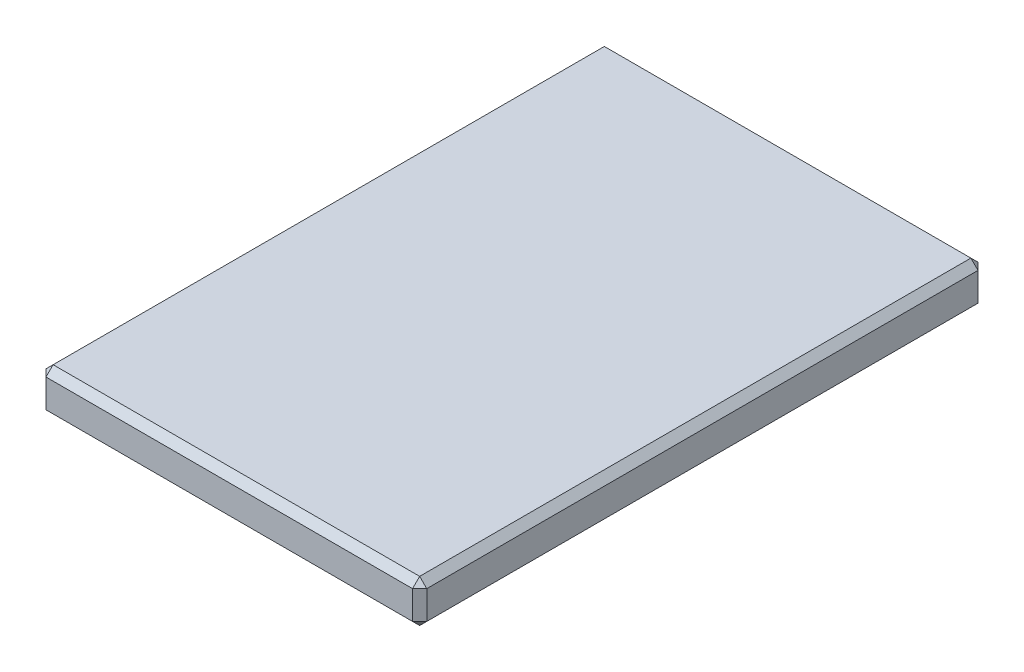
SolidWorks part; units mm, degrees
ref_plane "Front Plane" through (0, 0, 0) normal (0, 0, 1) x (1, 0, 0)
ref_plane "Top Plane" through (0, 0, 0) normal (0, 1, 0) x (1, 0, 0)
ref_plane "Right Plane" through (0, 0, 0) normal (1, 0, 0) x (0, 0, -1)
sketch "Sketch1" plane through (0, 0, 0) normal (0, 1, 0) x (1, 0, 0)
  line L1 (0, 0) -> (26.8, 0)
  line L2 (0, 0) -> (0, -39.8)
  line L3 (0, -39.8) -> (26.8, -39.8)
  line L4 (26.8, 0) -> (26.8, -39.8)
  dimension "D1" = 39.8
  dimension "D2" = 26.8
extrude "Boss-Extrude1" add sketch "Sketch1" along normal blind 3
chamfer "Chamfer1" distance 0.5 angle 45 12 edges at (0, 1.5, 0) (26.8, 1.5, 0) (0, 1.5, 39.8) (13.4, 0, 39.8) (0, 0, 19.9) (13.4, 0, 0) (26.8, 0, 19.9) (26.8, 1.5, 39.8) (13.4, 3, 0) (26.8, 3, 19.9) (13.4, 3, 39.8) (0, 3, 19.9)
